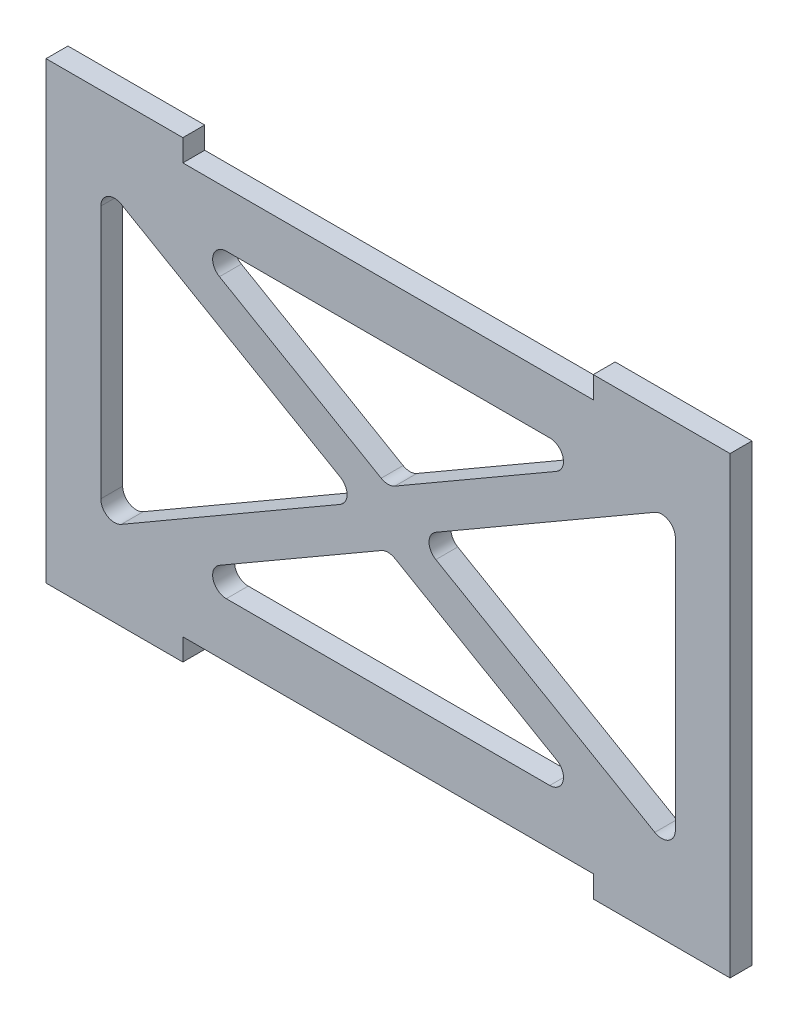
SolidWorks part; units mm, degrees
ref_plane "Front Plane" through (0, 0, 0) normal (0, 0, 1) x (1, 0, 0)
ref_plane "Top Plane" through (0, 0, 0) normal (0, 1, 0) x (1, 0, 0)
ref_plane "Right Plane" through (0, 0, 0) normal (1, 0, 0) x (0, 0, -1)
sketch "Sketch1" plane through (0, 0, 0) normal (0, 0, 1) x (1, 0, 0)
  line L1 (0, 0) -> (50, 0)
  line L2 (0, 0) -> (0, 30)
  line L3 (0, 30) -> (50, 30)
  line L4 (50, 0) -> (50, 30)
  dimension "D1" = 50
  dimension "D2" = 30
extrude "Boss-Extrude1" add sketch "Sketch1" along normal blind 1.6
sketch "Sketch2" plane through (0, 0, 1.6) normal (0, 0, 1) x (1, 0, 0)
  line L0 (0, 15) -> (50, 15) construction
  line L1 (0, 30) -> (10, 30)
  line L2 (0, 30) -> (0, 31.6)
  line L3 (0, 31.6) -> (10, 31.6)
  line L4 (10, 30) -> (10, 31.6)
  line L5 (0, 30) -> (0, 0) construction
  line L6 (50, 0) -> (50, 30) construction
  line L7 (40, 30) -> (40, 31.6)
  line L8 (50, 30) -> (0, 30) construction
  line L9 (25, 30) -> (25, 0) construction
  line L10 (0, 0) -> (50, 0) construction
  line L11 (50, 31.6) -> (40, 31.6)
  line L12 (50, 30) -> (50, 31.6)
  line L13 (50, 30) -> (40, 30)
  line L14 (50, 0) -> (40, 0)
  line L15 (50, 0) -> (50, -1.6)
  line L16 (50, -1.6) -> (40, -1.6)
  line L17 (40, 0) -> (40, -1.6)
  line L18 (10, 0) -> (10, -1.6)
  line L19 (0, -1.6) -> (10, -1.6)
  line L20 (0, 0) -> (0, -1.6)
  line L21 (0, 0) -> (10, 0)
  dimension "D1" = 10
  dimension "D2" = 1.6
extrude "Boss-Extrude2" add sketch "Sketch2" against normal up to surface (1.6 mm away) up to face at (25, 15, 0)
sketch "Sketch3" plane through (0, 0, 1.6) normal (0, 0, 1) x (1, 0, 0)
  line L0 (4, 26) -> (4, 4)
  line L1 (4, 4) -> (23, 15)
  line L2 (23, 15) -> (4, 26)
  line L3 (0, 31.6) -> (0, -1.6) construction
  line L4 (40, 30) -> (10, 30) construction
  line L5 (25, 30) -> (25, 0) construction
  line L6 (10, 0) -> (40, 0) construction
  line L7 (9.4545, 26) -> (40.5455, 26)
  line L9 (25, 17) -> (9.4545, 26)
  line L10 (0, 15) -> (50, 15) construction
  line L11 (50, -1.6) -> (50, 31.6) construction
  line L12 (25, 13) -> (9.4545, 4)
  line L13 (9.4545, 4) -> (40.5455, 4)
  line L14 (25, 13) -> (40.5455, 4)
  line L15 (25, 17) -> (40.5455, 26)
  line L16 (27, 15) -> (46, 26)
  line L17 (46, 4) -> (27, 15)
  line L18 (46, 26) -> (46, 4)
  point P11 (25, 15)
  point P23 (25, 4)
  point P24 (25, 26)
  dimension "D1" = 4
  dimension "D2" = 4
  dimension "D3" = 2
  dimension "D4" = 4
  dimension "D5" = 2
extrude "Cut-Extrude1" cut sketch "Sketch3" against normal through all
fillet "Fillet1" radius 1 12 edges at (40.5455, 4, 0.8) (23, 15, 0.8) (25, 17, 0.8) (46, 4, 0.8) (9.4545, 4, 0.8) (4, 4, 0.8) (27, 15, 0.8) (46, 26, 0.8) (4, 26, 0.8) (25, 13, 0.8) (40.5455, 26, 0.8) (9.4545, 26, 0.8)
